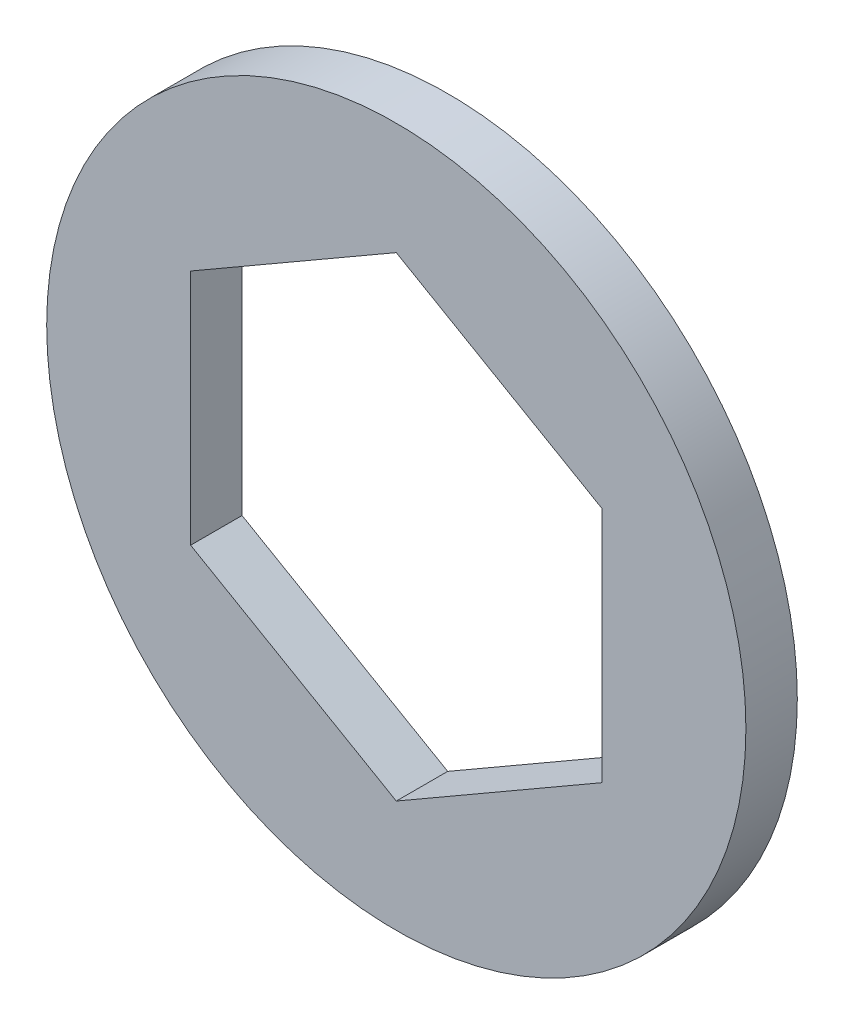
SolidWorks part; units mm, degrees
material "Nylon 101"
ref_plane "Front Plane" through (0, 0, 0) normal (0, 0, 1) x (1, 0, 0)
ref_plane "Top Plane" through (0, 0, 0) normal (0, 1, 0) x (1, 0, 0)
ref_plane "Right Plane" through (0, 0, 0) normal (1, 0, 0) x (0, 0, -1)
sketch "Sketch1" plane through (0, 0, 0) normal (0, 0, 1) x (1, 0, 0)
  line L1 (0, 7.3323) -> (-6.35, 3.6662)
  line L2 (-6.35, 3.6662) -> (-6.35, -3.6662)
  line L3 (-6.35, -3.6662) -> (0, -7.3323)
  line L4 (0, -7.3323) -> (6.35, -3.6662)
  line L5 (6.35, -3.6662) -> (6.35, 3.6662)
  line L6 (6.35, 3.6662) -> (0, 7.3323)
  circle A0 centre (0, 0) radius 6.35 construction
  circle A1 centre (0, 0) radius 10.795
  dimension "D1" = 12.7
  dimension "D2" = 21.59
extrude "Boss-Extrude1" add sketch "Sketch1" along normal mid plane 1.5875
